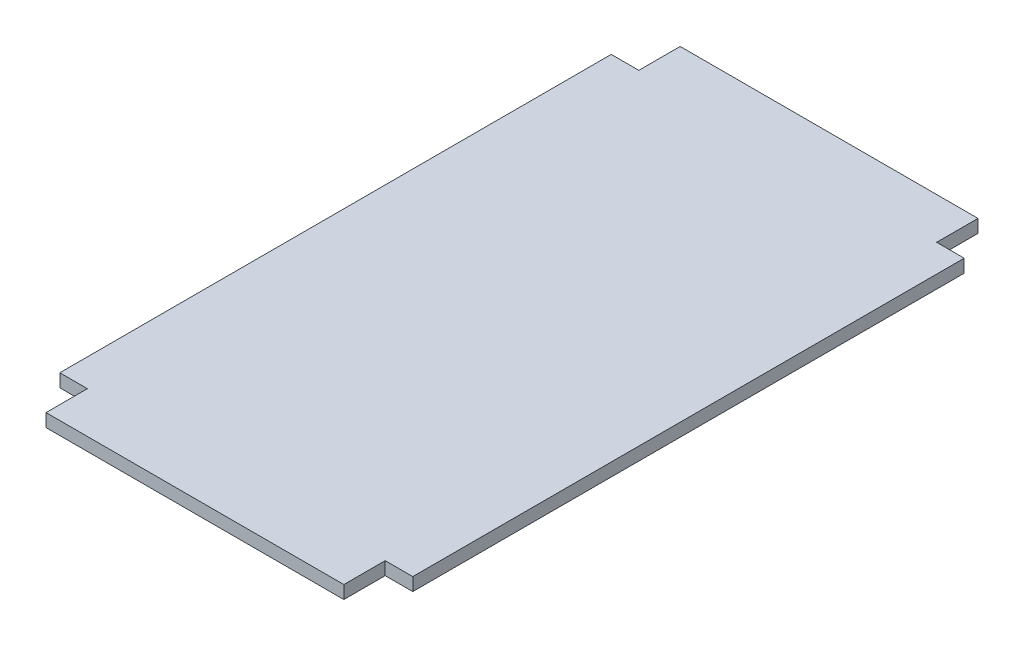
SolidWorks part; units mm, degrees
ref_plane "Front Plane" through (0, 0, 0) normal (0, 0, 1) x (1, 0, 0)
ref_plane "Top Plane" through (0, 0, 0) normal (0, 1, 0) x (1, 0, 0)
ref_plane "Right Plane" through (0, 0, 0) normal (1, 0, 0) x (0, 0, -1)
sketch "Sketch1" plane through (0, 0, 0) normal (0, 1, 0) x (1, 0, 0)
  line L0 (-40.6471, 66.4972) -> (40.6471, 66.4972) construction
  line L1 (40.6471, -73.025) -> (-40.6471, -73.025)
  line L2 (40.6471, -73.025) -> (40.6471, 73.025)
  line L3 (40.6471, 73.025) -> (-40.6471, 73.025)
  line L4 (-40.6471, -73.025) -> (-40.6471, 73.025)
  line L5 (40.6471, -73.025) -> (-40.6471, 73.025) construction
  line L6 (40.6471, 73.025) -> (-40.6471, -73.025) construction
  line L7 (-40.6471, -66.4972) -> (40.6471, -66.4972) construction
  line L8 (-40.6471, 66.4972) -> (-40.6471, -66.4972) construction
  line L9 (40.6471, 66.4972) -> (40.6471, -66.4972) construction
  line L20 (-40.6471, -73.025) -> (-34.2971, -73.025)
  line L29 (-40.6471, -73.025) -> (-40.6471, -63.5)
  line L34 (-40.6471, -63.5) -> (-34.2971, -63.5)
  line L35 (-34.2971, -73.025) -> (-34.2971, -63.5)
  line L36 (40.6471, -73.025) -> (34.2971, -73.025)
  line L37 (40.6471, -73.025) -> (40.6471, -63.5)
  line L38 (40.6471, -63.5) -> (34.2971, -63.5)
  line L39 (34.2971, -73.025) -> (34.2971, -63.5)
  line L40 (-40.6471, 73.025) -> (-34.2971, 73.025)
  line L41 (-40.6471, 73.025) -> (-40.6471, 63.5)
  line L42 (-40.6471, 63.5) -> (-34.2971, 63.5)
  line L43 (-34.2971, 73.025) -> (-34.2971, 63.5)
  line L44 (40.6471, 73.025) -> (34.2971, 73.025)
  line L45 (40.6471, 73.025) -> (40.6471, 63.5)
  line L46 (40.6471, 63.5) -> (34.2971, 63.5)
  line L47 (34.2971, 73.025) -> (34.2971, 63.5)
  point P0 (0, 0)
  point P10 (40.6471, 0)
  point P11 (40.6471, 0)
  dimension "D1" = 81.2943
  dimension "D2" = 146.05
  dimension "D3" = 132.9944
  dimension "D4" = 6.35
  dimension "D5" = 127
extrude "Boss-Extrude1" add sketch "Sketch1" along normal blind 2.9972
